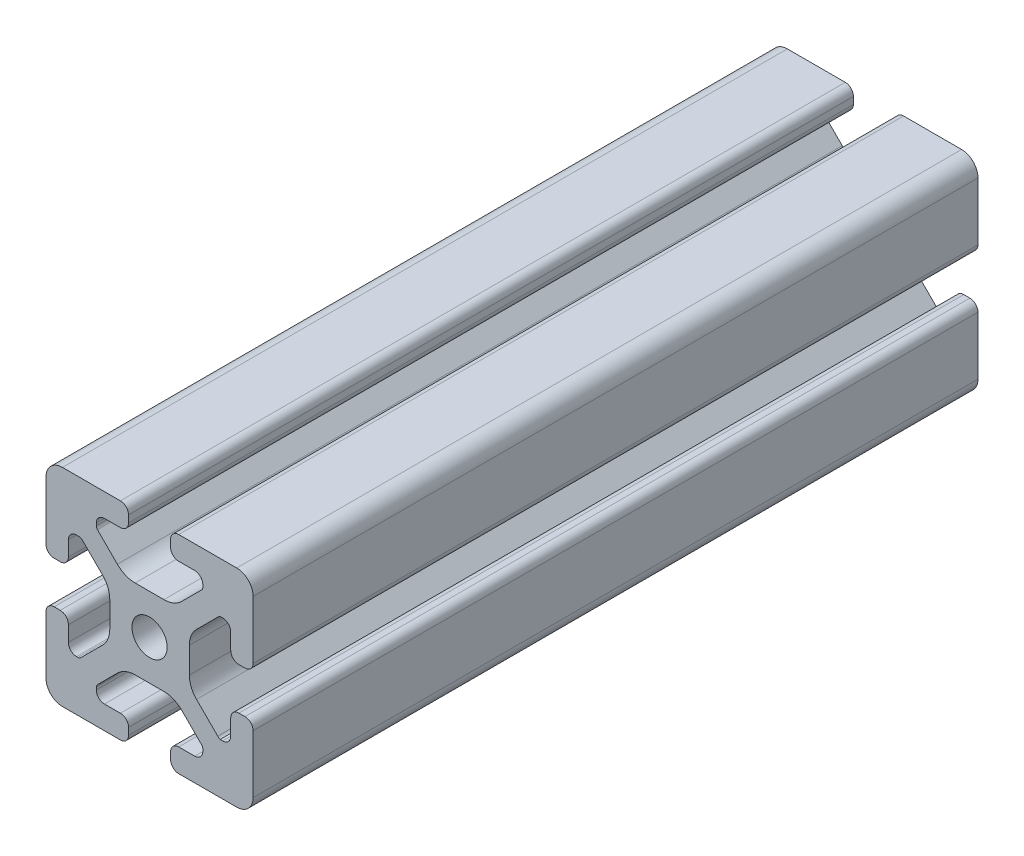
SolidWorks part; units mm, degrees
material "6061 Alloy"
ref_plane "Front Plane" through (0, 0, 0) normal (0, 0, 1) x (1, 0, 0)
ref_plane "Top Plane" through (0, 0, 0) normal (0, 1, 0) x (1, 0, 0)
ref_plane "Right Plane" through (0, 0, 0) normal (1, 0, 0) x (0, 0, -1)
sketch "Sketch1" plane through (0, 0, 0) normal (0, 0, 1) x (1, 0, 0)
  line L0 (0, 19.7407) -> (0, -19.7407) construction
  line L1 (19.0335, 0) -> (-20.7246, 0) construction
  line L2 (-8.715, -15.5246) -> (-5.63, -15.5246)
  line L3 (-10.285, -13.9546) -> (-10.285, -13.4925)
  line L4 (-6.2171, -9.1098) -> (-10.0624, -12.9551)
  line L5 (2.7773, -7.685) -> (-2.7773, -7.685)
  line L6 (10.0624, -12.9551) -> (6.2171, -9.1098)
  line L7 (10.285, -13.9546) -> (10.285, -13.4925)
  line L8 (5.63, -15.5246) -> (8.715, -15.5246)
  line L9 (4.06, -18.43) -> (4.06, -17.0946)
  line L10 (-4.06, -18.43) -> (-4.06, -17.0946)
  line L11 (15.68, -8.7154) -> (15.68, -5.63)
  line L12 (-14.11, -10.2854) -> (-13.8169, -10.2854)
  line L13 (20, -16.83) -> (20, -5.63)
  line L14 (20, 5.63) -> (20, 13.0011)
  line L15 (-16.83, 20) -> (-5.63, 20)
  line L16 (5.63, 20) -> (12.9796, 20)
  line L18 (-8.715, 15.5246) -> (-5.63, 15.5246)
  line L19 (-20, -17.0184) -> (-20, -5.7579)
  line L20 (-20, 5.573) -> (-20, 13.0045)
  line L21 (-15.68, -8.7154) -> (-15.68, -5.7579)
  line L23 (-16.6746, -20) -> (-5.63, -20)
  line L24 (5.63, -20) -> (13, -20)
  line L53 (14.11, -10.2854) -> (13.6201, -10.2854)
  line L54 (13.1637, -9.947) -> (9.0762, -5.8595)
  line L55 (7.685, -2.5008) -> (7.685, 2.5008)
  line L56 (9.0762, 5.8595) -> (13.2795, 10.0628)
  line L57 (13.8169, 10.2854) -> (14.11, 10.2854)
  line L58 (15.68, 8.7154) -> (15.68, 5.63)
  line L59 (17.25, 4.06) -> (18.43, 4.06)
  line L61 (20, 13.0011) -> (20, 16.83)
  line L62 (16.83, 20) -> (12.9796, 20)
  line L64 (4.06, 18.43) -> (4.06, 17.0946)
  line L65 (5.63, 15.5246) -> (8.715, 15.5246)
  line L66 (10.285, 13.9546) -> (10.285, 13.4925)
  line L67 (10.0624, 12.9551) -> (6.2171, 9.1098)
  line L68 (2.7773, 7.685) -> (-2.7773, 7.685)
  line L69 (-6.2171, 9.1098) -> (-10.0624, 12.9551)
  line L70 (-10.285, 13.4925) -> (-10.285, 13.9546)
  line L72 (-4.06, 17.0946) -> (-4.06, 18.43)
  line L75 (-20, 16.83) -> (-20, 13.0045)
  line L77 (-18.43, 4.003) -> (-17.25, 4.003)
  line L78 (-15.68, 5.573) -> (-15.68, 8.4757)
  line L79 (-14.0552, 10.0447) -> (-13.7199, 10.033)
  line L80 (-13.0405, 9.8238) -> (-9.0762, 5.8595)
  line L81 (-7.685, 2.5008) -> (-7.685, -2.5008)
  line L82 (-9.0762, -5.8595) -> (-13.2795, -10.0628)
  line L85 (-17.25, -4.1204) -> (-18.43, -4.1204)
  line L100 (13, -20) -> (16.83, -20)
  line L103 (18.43, -4.06) -> (17.25, -4.06)
  arc A0 (-5.63, -15.5246) -> (-4.06, -17.0946) centre (-5.63, -17.0946) cw
  arc A1 (-8.715, -15.5246) -> (-10.285, -13.9546) centre (-8.715, -13.9546) cw
  arc A2 (-10.285, -13.4925) -> (-10.0624, -12.9551) centre (-9.525, -13.4925) cw
  arc A3 (-6.2171, -9.1098) -> (-2.7773, -7.685) centre (-2.7773, -12.5496) cw
  arc A4 (2.7773, -7.685) -> (6.2171, -9.1098) centre (2.7773, -12.5496) cw
  arc A5 (10.0624, -12.9551) -> (10.285, -13.4925) centre (9.525, -13.4925) cw
  arc A6 (10.285, -13.9546) -> (8.715, -15.5246) centre (8.715, -13.9546) cw
  arc A7 (4.06, -17.0946) -> (5.63, -15.5246) centre (5.63, -17.0946) cw
  arc A8 (5.63, -20) -> (4.06, -18.43) centre (5.63, -18.43) cw
  arc A9 (-4.06, -18.43) -> (-5.63, -20) centre (-5.63, -18.43) cw
  circle A45 centre (0, 0) radius 3.4
  arc A46 (17.25, -4.06) -> (15.68, -5.63) centre (17.25, -5.63) ccw
  arc A47 (14.11, -10.2854) -> (15.68, -8.7154) centre (14.11, -8.7154) ccw
  arc A48 (13.1637, -9.947) -> (13.6201, -10.2854) centre (13.8117, -9.55) ccw
  arc A49 (7.685, -2.5008) -> (9.0762, -5.8595) centre (12.435, -2.5008) ccw
  arc A50 (9.0762, 5.8595) -> (7.685, 2.5008) centre (12.435, 2.5008) ccw
  arc A51 (13.8169, 10.2854) -> (13.2795, 10.0628) centre (13.8169, 9.5254) ccw
  arc A52 (15.68, 8.7154) -> (14.11, 10.2854) centre (14.11, 8.7154) ccw
  arc A53 (15.68, 5.63) -> (17.25, 4.06) centre (17.25, 5.63) ccw
  arc A54 (18.43, 4.06) -> (20, 5.63) centre (18.43, 5.63) ccw
  arc A55 (20, 16.83) -> (16.83, 20) centre (16.83, 16.83) ccw
  arc A56 (5.63, 20) -> (4.06, 18.43) centre (5.63, 18.43) ccw
  arc A57 (4.06, 17.0946) -> (5.63, 15.5246) centre (5.63, 17.0946) ccw
  arc A58 (10.285, 13.9546) -> (8.715, 15.5246) centre (8.715, 13.9546) ccw
  arc A59 (10.0624, 12.9551) -> (10.285, 13.4925) centre (9.525, 13.4925) ccw
  arc A60 (2.7773, 7.685) -> (6.2171, 9.1098) centre (2.7773, 12.5496) ccw
  arc A61 (-6.2171, 9.1098) -> (-2.7773, 7.685) centre (-2.7773, 12.5496) ccw
  arc A62 (-10.285, 13.4925) -> (-10.0624, 12.9551) centre (-9.525, 13.4925) ccw
  arc A63 (-8.715, 15.5246) -> (-10.285, 13.9546) centre (-8.715, 13.9546) ccw
  arc A64 (-5.63, 15.5246) -> (-4.06, 17.0946) centre (-5.63, 17.0946) ccw
  arc A65 (-4.06, 18.43) -> (-5.63, 20) centre (-5.63, 18.43) ccw
  arc A66 (-16.83, 20) -> (-20, 16.83) centre (-16.83, 16.83) ccw
  arc A67 (-20, 5.573) -> (-18.43, 4.003) centre (-18.43, 5.573) ccw
  arc A68 (-17.25, 4.003) -> (-15.68, 5.573) centre (-17.25, 5.573) ccw
  arc A69 (-14.0552, 10.0447) -> (-15.68, 8.4757) centre (-14.11, 8.4757) ccw
  arc A70 (-13.0405, 9.8238) -> (-13.7199, 10.033) centre (-13.5779, 9.2864) ccw
  arc A71 (-7.685, 2.5008) -> (-9.0762, 5.8595) centre (-12.435, 2.5008) ccw
  arc A72 (-9.0762, -5.8595) -> (-7.685, -2.5008) centre (-12.435, -2.5008) ccw
  arc A73 (-13.8169, -10.2854) -> (-13.2795, -10.0628) centre (-13.8169, -9.5254) ccw
  arc A74 (-15.68, -8.7154) -> (-14.11, -10.2854) centre (-14.11, -8.7154) ccw
  arc A75 (-15.68, -5.7579) -> (-17.25, -4.1204) centre (-17.2485, -5.6904) ccw
  arc A76 (-18.43, -4.1204) -> (-20, -5.7579) centre (-18.4315, -5.6904) ccw
  arc A77 (-20, -17.0184) -> (-16.6746, -20) centre (-16.8354, -16.8341) ccw
  arc A88 (16.83, -20) -> (20, -16.83) centre (16.83, -16.83) ccw
  arc A89 (20, -5.63) -> (18.43, -4.06) centre (18.43, -5.63) ccw
  dimension "D2" = 6.8
  dimension "D7" = 20.57
  dimension "D1" = 40
  dimension "D3" = 4.32
  dimension "D4" = 15.37
  dimension "D5" = 20
  dimension "D6" = 4.32
  dimension "D9" = 15.37
extrude "Extrude1" add sketch "Sketch1" against normal blind 140
equation "\"PinDiameter\"= 0"
equation "\"WallThickness\"= 0.5cm"
equation "\"BottomPlateX\"= 100cm"
equation "\"BottomPlateZ\"= 70cm"
equation "\"BottomPlateHoleD\"=((\"ArmPlateX\")^2+(\"ArmPlateDepth\")^2)^.5+ 10mm"
equation "\"ActuatorL\"= 35cm"
equation "\"ActuatorPinD\"= 6.35mm"
equation "\"ActuatorPinL\"= 15cm"
equation "\"Box-X\"= 40cm"
equation "\"Box-Z\"= 20cm"
equation "\"Box-Y\"= 30cm"
equation "\"ArmPlateThickness\"= 1cm"
equation "\"ArmPlateX\"= 50cm"
equation "\"ArmPlateDepth\"= 20cm"
equation "\"Arm1X\"= 5cm"
equation "\"Arm1L\"= 60cm"
equation "\"Arm2GAP\"= 5cm"
equation "\"Arm2L\"= 60cm"
equation "\"Arm2H\"= 5cm"
equation "\"Arm2Extension\"= 5cm"
equation "\"Arm3GAP\"= 5cm"
equation "\"Arm3L\"= 60cm"
equation "\"Arm3H\"= 5cm"
equation "\"Pin1-2L\"= \"Arm2GAP\" + (2 * \"WallThickness\")"
equation "\"Pin2-3L\"= \"Arm3GAP\" + (4 * \"WallThickness\")"
equation "\"DCMotor1D\"= 65mm"
equation "\"DCMotor1L\"= 215mm"
equation "\"DCMotor1ShaftL\"= 30mm"
equation "\"DCMotor2X\"= 68mm"
equation "\"DCMotor2D\"= 65mm"
equation "\"DCMotor2L\"= 215mm"
equation "\"DCMotor2ShaftL\"= 30mm"
equation "\"DCMotor2ShaftD\"= 15mm"
equation "\"BenchDepth\"= 5cm"
equation "\"BenchH\"= 10cm"
equation "\"BenchL\"= 15cm"
equation "\"PillowBlockW\"= 5cm"
equation "\"PillowBlockCenterH\"= \"DCMotor2X\"/2"
equation "\"EncoderRadius\"= 19mm"
equation "\"EncoderShaftL\"= 15mm"
equation "\"EncoderL\"= 33mm"
equation "\"EncoderHousingThickness\"= 7.5mm"
equation "\"TurntableID\"= 70mm"
equation "\"TurntableInner2*t\" = (\"TurntableOD\"-\"TurntableID\")*.25 - .5mm"
equation "\"TurntableInnerHoleRadius\"= \"TurntableID\"*.5 + \"TurntableInner2*t\"*.5"
equation "\"TurntableOD\"= 120mm"
equation "\"TurntableOuterHoleRadius\" = \"TurntableOD\"*.5 - ((\"TurntableOD\"-\"TurntableID\")*.25-.5mm)*.5"
equation "\"4040Height\" = 30cm"
equation "\"LENGTH@Extrude1\"=\"TurntableOD\"+2cm"
